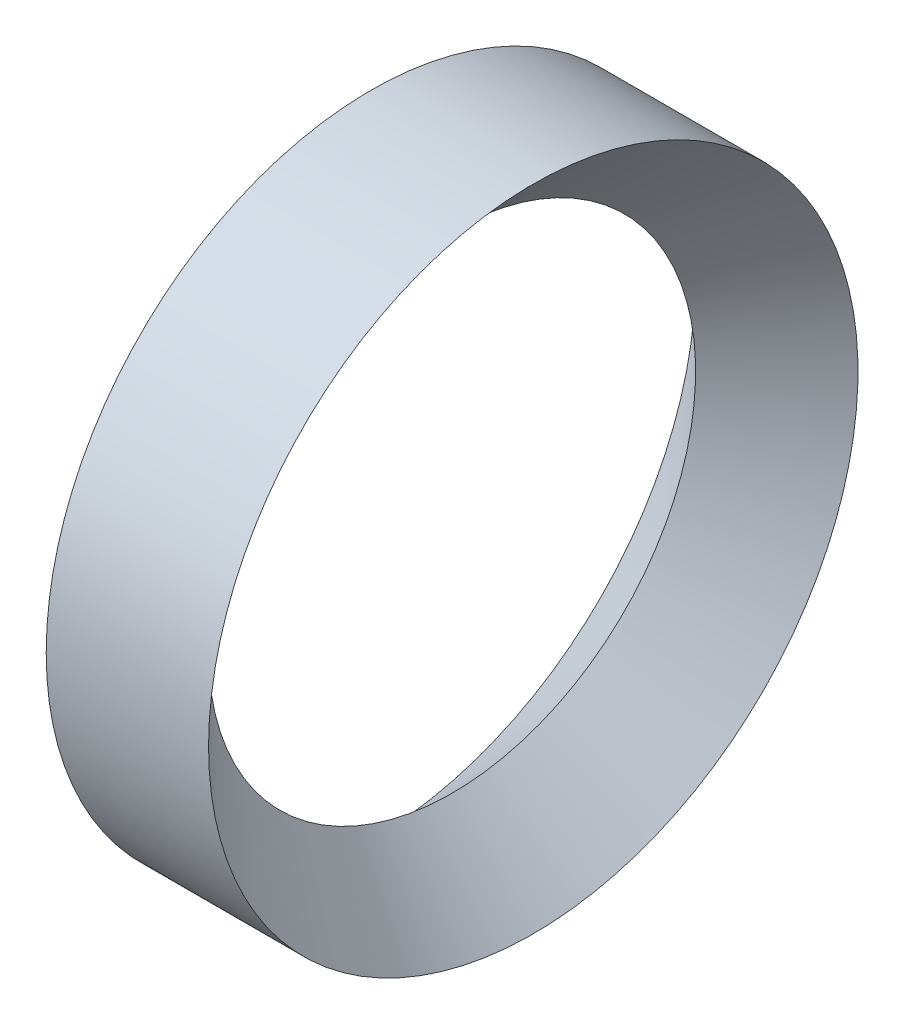
SolidWorks part; units mm, degrees
ref_plane "前视基准面" through (0, 0, 0) normal (0, 0, 1) x (1, 0, 0)
ref_plane "上视基准面" through (0, 0, 0) normal (0, 1, 0) x (1, 0, 0)
ref_plane "右视基准面" through (0, 0, 0) normal (1, 0, 0) x (0, 0, -1)
sketch "草图1" plane through (0, 0, 0) normal (0, 0, 1) x (1, 0, 0)
  line L0 (-52.3395, 0) -> (51.6615, 0) construction
  line L1 (0, 8) -> (2, 8)
  line L2 (2, 8) -> (0, 6)
  line L3 (0, 33.8175) -> (0, -57.9865) construction
  line L4 (-2, 8) -> (0, 6)
  line L5 (0, 8) -> (-2, 8)
  point P8 (0.2814, 26.1508)
  point P9 (0.1593, 20.3317)
  dimension "D1" = 45
  dimension "D2" = 6
  dimension "D3" = 4
revolve "旋转1" add sketch "草图1" angle 360 about L0
